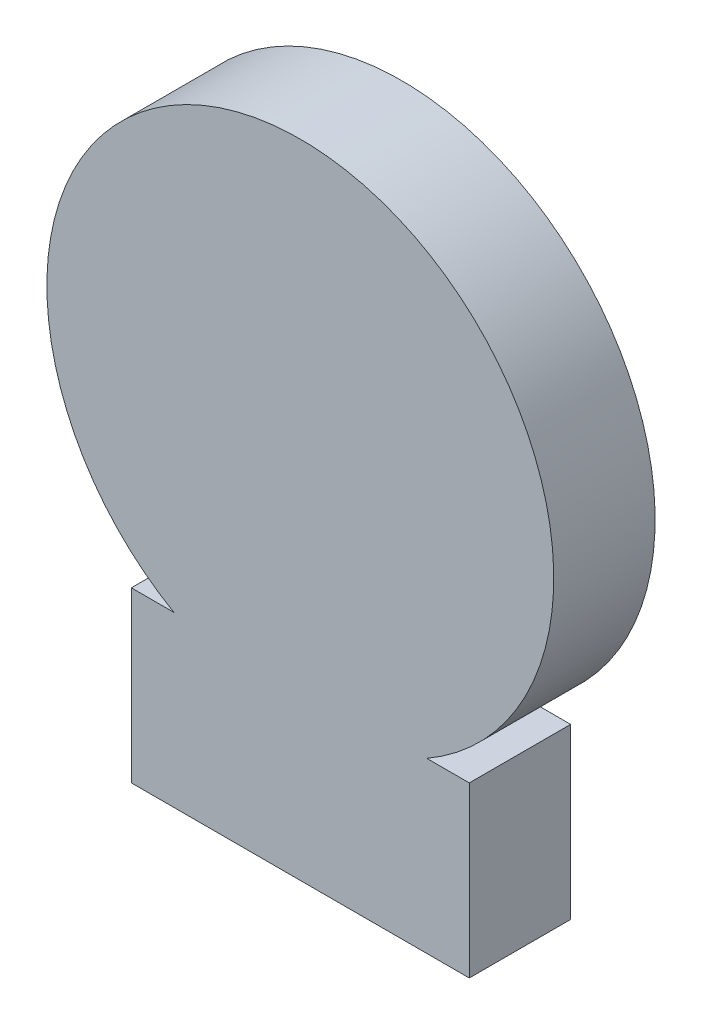
SolidWorks part; units mm, degrees
ref_plane "Plan de face" through (0, 0, 0) normal (0, 0, 1) x (1, 0, 0)
ref_plane "Plan de dessus" through (0, 0, 0) normal (0, 1, 0) x (1, 0, 0)
ref_plane "Plan de droite" through (0, 0, 0) normal (1, 0, 0) x (0, 0, -1)
sketch "Esquisse1" plane through (0, 0, 0) normal (0, 0, 1) x (1, 0, 0)
  line L1 (10, -5) -> (-10, -5)
  line L2 (10, -5) -> (10, 5)
  line L3 (10, 5) -> (-10, 5)
  line L4 (-10, -5) -> (-10, 5)
  line L5 (10, -5) -> (-10, 5) construction
  line L6 (10, 5) -> (-10, -5) construction
  point P0 (0, 0)
extrude "Boss.-Extru.1" add sketch "Esquisse1" along normal blind 6
sketch "Esquisse2" plane through (0, 0, 6) normal (0, 0, 1) x (1, 0, 0)
  circle A0 centre (0, 18) radius 15
extrude "Boss.-Extru.2" add sketch "Esquisse2" against normal blind 6
